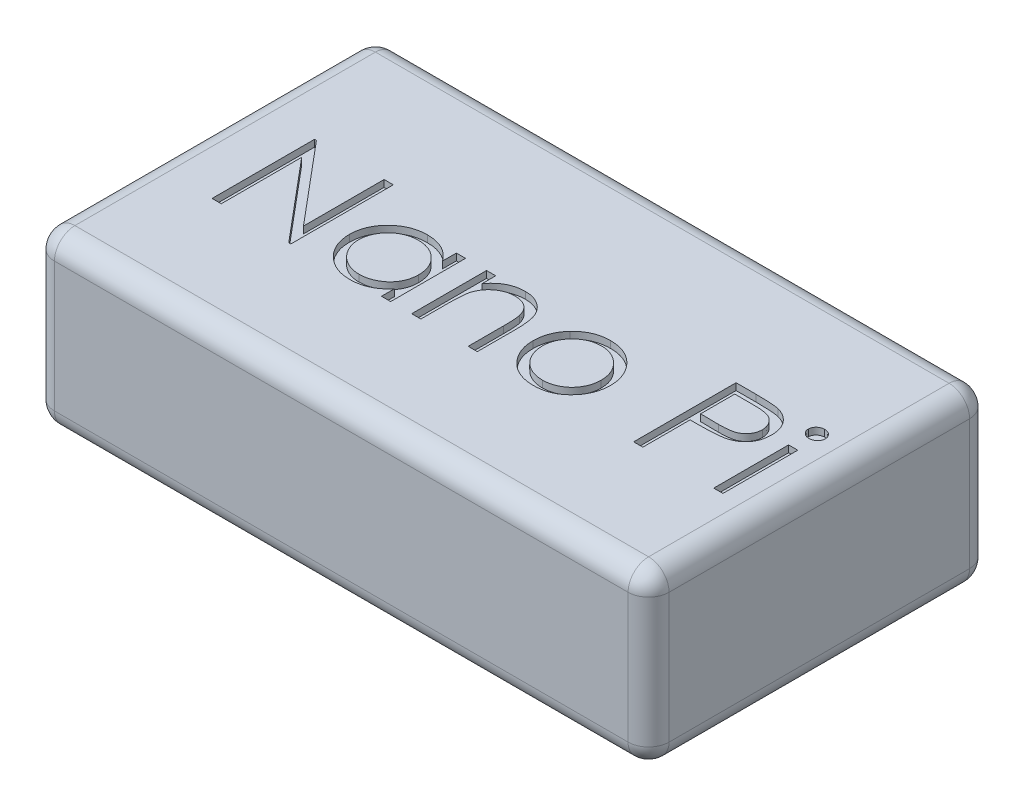
SolidWorks part; units mm, degrees
ref_plane "Front" through (0, 0, 0) normal (0, 0, 1) x (1, 0, 0)
ref_plane "Top" through (0, 0, 0) normal (0, 1, 0) x (1, 0, 0)
ref_plane "Right" through (0, 0, 0) normal (1, 0, 0) x (0, 0, -1)
sketch "Sketch1" plane through (0, 0, 0) normal (0, 1, 0) x (1, 0, 0)
  line L1 (-48.5915, 24.4718) -> (41.4085, 24.4718)
  line L2 (-48.5915, 24.4718) -> (-48.5915, -25.5282)
  line L3 (-48.5915, -25.5282) -> (41.4085, -25.5282)
  line L4 (41.4085, 24.4718) -> (41.4085, -25.5282)
  dimension "D1" = 50
  dimension "D2" = 90
  dimension "D3" = 41.4085
  dimension "D4" = 24.4718
extrude "Boss-Extrude1" add sketch "Sketch1" along normal blind 25
fillet "Fillet1" radius 3 12 edges at (-3.5915, 0, 25.5282) (41.4085, 0, 0.5282) (-3.5915, 0, -24.4718) (-48.5915, 0, 0.5282) (-3.5915, 25, -24.4718) (41.4085, 25, 0.5282) (-3.5915, 25, 25.5282) (-48.5915, 25, 0.5282) (41.4085, 12.5, -24.4718) (41.4085, 12.5, 25.5282) (-48.5915, 12.5, -24.4718) (-48.5915, 12.5, 25.5282)
sketch "Sketch2" plane through (0, 25, 0) normal (0, 1, 0) x (1, 0, 0)
  line L2 (38.4085, -22.5282) -> (38.4085, 21.4718) construction
  line L3 (38.4085, 21.4718) -> (-45.5915, 21.4718) construction
  text T0 "Nano Pi" font "Century Gothic" height 15
  dimension "D1" = 79.3239
  dimension "D2" = 30.5192
extrude "Cut-Extrude1" cut sketch "Sketch2" against normal blind 1
